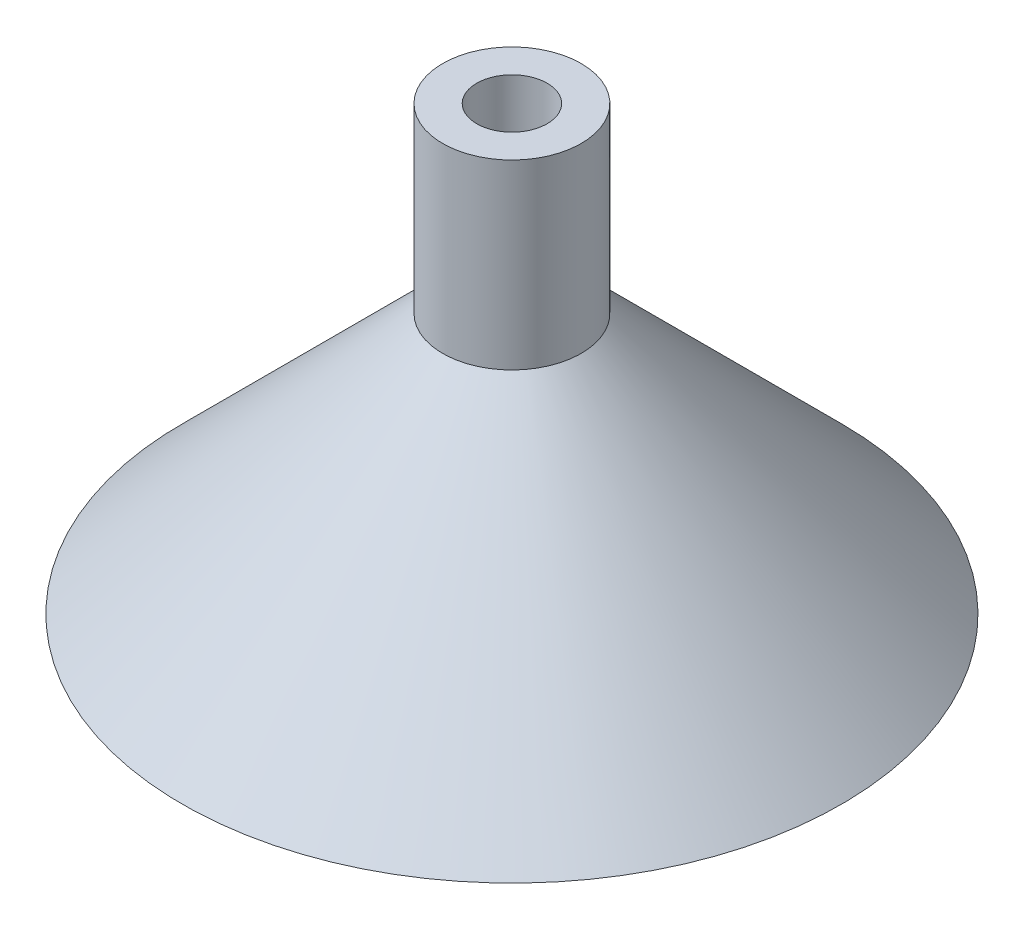
SolidWorks part; units mm, degrees
ref_plane "Front Plane" through (0, 0, 0) normal (0, 0, 1) x (1, 0, 0)
ref_plane "Top Plane" through (0, 0, 0) normal (0, 1, 0) x (1, 0, 0)
ref_plane "Right Plane" through (0, 0, 0) normal (1, 0, 0) x (0, 0, -1)
sketch "Sketch2" plane through (0, 0, 0) normal (0, 0, 1) x (1, 0, 0)
  line L0 (25.323, 0) -> (29, 0)
  line L1 (29, 0) -> (6.096, 22.904)
  line L2 (6.096, 22.904) -> (6.096, 38.904)
  line L3 (6.096, 38.904) -> (3.096, 38.904)
  line L4 (3.096, 38.904) -> (3.096, 22.227)
  line L5 (3.096, 22.227) -> (25.323, 0)
  line L6 (0, 0) -> (0, 50000) construction
  line L7 (-3.096, 22.227) -> (-25.323, 0) construction
  line L8 (-3.096, 38.904) -> (-3.096, 22.227) construction
  line L9 (-6.096, 38.904) -> (-3.096, 38.904) construction
  line L10 (-6.096, 22.904) -> (-6.096, 38.904) construction
  line L11 (-29, 0) -> (-6.096, 22.904) construction
  line L12 (-25.323, 0) -> (-29, 0) construction
  dimension "D1" = 3
  dimension "D2" = 2.6
  dimension "D3" = 12.192
  dimension "D4" = 58
  dimension "D5" = 16
  dimension "D6" = 45
revolve "Revolve1" add sketch "Sketch2" angle 360 about L6
